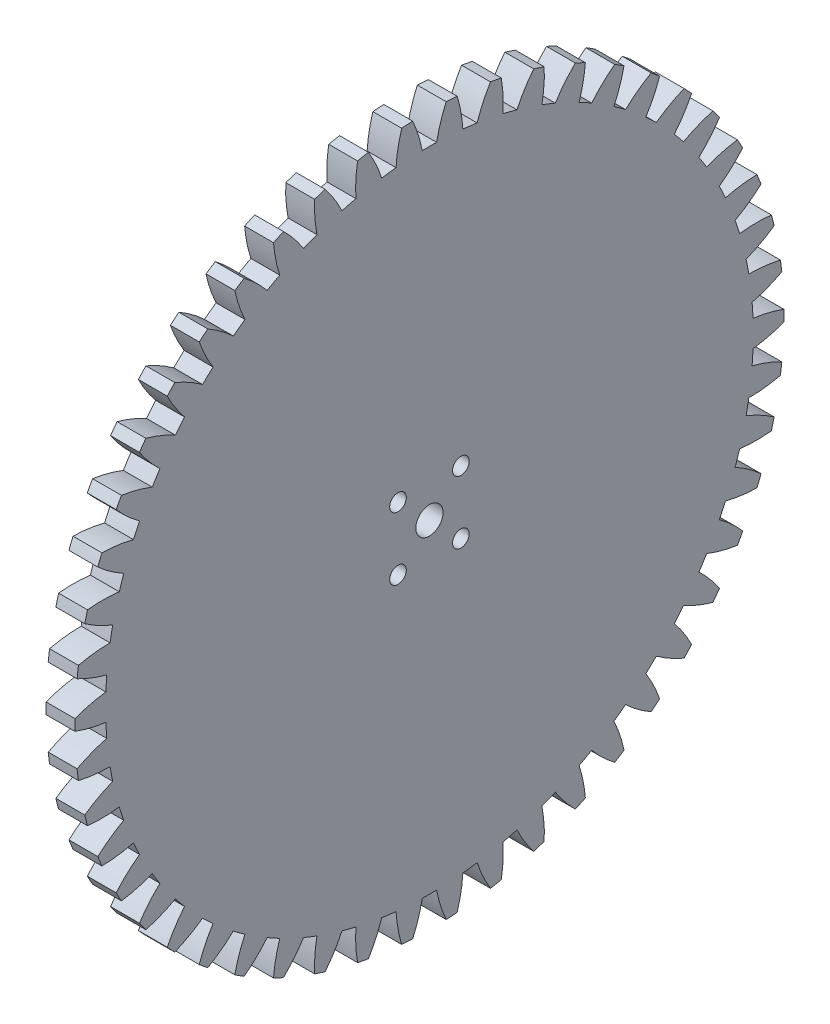
SolidWorks part; units mm, degrees
ref_plane "Plane1" through (0, 0, 0) normal (0, 0, 1) x (1, 0, 0)
ref_plane "Plane2" through (0, 0, 0) normal (0, 1, 0) x (1, 0, 0)
ref_plane "Plane3" through (0, 0, 0) normal (1, 0, 0) x (0, 0, -1)
sketch "HoldingSke" plane through (0, 0, 0) normal (0, 1, 0) x (1, 0, 0)
  line L0 (0, 0) -> (0.2143, -0.2553)
  line L1 (-15, 0) -> (100, 0) construction
  line L2 (0, 0) -> (-2.1039, 2.3779)
  line L3 (0, 0) -> (-11.863, 4.5341)
  line L4 (0, 0) -> (5.5511, 6.6156)
  line L5 (0, 0) -> (-46.8476, -17.4728)
  line L6 (0, 0) -> (-5.2639, -3.5516)
  line L7 (-2.1039, 2.3779) -> (8.6586, 51.2061)
  line L8 (-76.2, 54.61) -> (-75.2, 54.61)
  line L9 (-67.7845, 28.3722) -> (-49.3413, 33.142)
  line L10 (-76.2, 71.12) -> (104.1128, 71.12)
  line L11 (0, 0) -> (-6.35, 0)
  line L12 (-76.2, 101.6) -> (-76.093, 101.6)
  line L13 (24.9733, 27.94) -> (52.9518, 28.4284)
  line L14 (24.9733, 27.94) -> (24.9743, 27.94)
  line L15 (24.9733, 27.94) -> (100.4006, 29.5858)
  line L16 (-63.627, -3) -> (-12.827, -3)
  circle A0 centre (0, 0) radius 3
  circle A1 centre (0, 0) radius 37.5
  circle A2 centre (0, 0) radius 37.5
  circle A3 centre (0, 0) radius 3
  dimension "MHD" = 75
  dimension "Hub_dia" = 75
  dimension "Bore" = 6
  dimension "MBD" = 6
  dimension "Num_teeth" = 50
  dimension "Pitch" = 0.3333
  dimension "Overall_len" = 50
  dimension "Show_teeth" = 50
  dimension "Thickness" = 6.35
  dimension "OAL" = 50.0003
  dimension "T_dim" = 1
  dimension "Ap" = 14.5
  dimension "H" = 19.05
  dimension "Pitch_radius" = 180.3128
  dimension "Width" = 6.35
  dimension "Backlash" = 0.107
  dimension "Addendum_fac" = 1
  dimension "Dedendum_fac" = 1.25
  dimension "Clearance_fac" = 0.25
  dimension "Dedendum_add" = 0.001
  dimension "Module" = 3
sketch "BasProSke" plane through (0, 0, 0) normal (0, 1, 0) x (1, 0, 0)
  line L0 (-10, 0) -> (60, 0) construction
  line L1 (0, 0) -> (0, 78)
  line L2 (0, 0) -> (6.35, 0)
  line L3 (6.35, 0) -> (6.35, 78)
  line L4 (6.35, 78) -> (0, 78)
  dimension "Thickness" = 6.35
  dimension "Diameter" = 156
revolve "Base-Revolve" add sketch "BasProSke" angle 360 about L0
sketch "TooCutSke" plane through (0, 0, 0) normal (1, 0, 0) x (0, 0, -1)
  line L1 (0, 0) -> (0, 107) construction
  line L2 (0, 0) -> (-2.543, 74.9569) construction
  line L3 (0, 0) -> (-9.4146, 149.6414) construction
  line L4 (-2.543, 74.9569) -> (-4.7073, 74.8207) construction
  arc A0 (1.5844, 71.2314) -> (-1.5844, 71.2314) centre (0, 0) ccw
  arc A1 (3.6968, 77.9378) -> (-3.6968, 77.9378) centre (0, 0) ccw
  circle A2 centre (0, 0) radius 75 construction
  circle A3 centre (0, 0) radius 72.6111 construction
  arc A4 (-1.5844, 71.2314) -> (-3.6968, 77.9378) centre (-31.0576, 65.6338) ccw
  arc A5 (3.6968, 77.9378) -> (1.5844, 71.2314) centre (31.0576, 65.6338) ccw
  dimension "Root_dia" = 142.498
  dimension "Overcut_dia" = 156.0508
  dimension "Pitch_dia" = 150
  dimension "Base_dia" = 145.2221
  dimension "Flank_rad" = 30
  dimension "Half_ang" = 3.6
  dimension "Half_CT" = 2.1686
extrude "ToothCut" cut sketch "TooCutSke" along normal through all
fillet "Breaks" [suppressed] radius 0.06
fillet "RootFillets" [suppressed] radius 0.751
pattern_circular "TeethCuts" count 50 over 360 about axis through (0, 0, 0) along (1, 0, 0) of "ToothCut", "RootFillets", "Breaks"
sketch "HubNeaOneSke" plane through (0, 0, 0) normal (-1, 0, 0) x (0, 0, 1)
  circle A0 centre (0, 0) radius 37.5
  dimension "Diameter" = 75
extrude "HubNearOne" [suppressed] add sketch "HubNeaOneSke" along normal blind 43.6503
sketch "HubNeaBotSke" plane through (0, 0, 0) normal (-1, 0, 0) x (0, 0, 1)
  circle A0 centre (0, 0) radius 37.5
  dimension "Diameter" = 75
extrude "HubNearBoth" [suppressed] add sketch "HubNeaBotSke" along normal blind 21.8251
ref_plane "FarPln" through (6.35, 0, 0) normal (1, 0, 0) x (0, 0, -1)
sketch "HubFarSke" plane through (6.35, 0, 0) normal (1, 0, 0) x (0, 0, -1)
  circle A0 centre (0, 0) radius 37.5
  dimension "Diameter" = 75
extrude "HubFar" [suppressed] add sketch "HubFarSke" along normal blind 21.8251
sketch "BorSke" plane through (0, 0, 0) normal (1, 0, 0) x (0, 0, -1)
  circle A0 centre (0, 0) radius 3
  dimension "Diameter" = 6
extrude "Bore" cut sketch "BorSke" along normal mid plane 100.0005
sketch "KeySke" plane through (0, 0, 0) normal (1, 0, 0) x (0, 0, -1)
  line L0 (-1, 0) -> (-1, 4)
  line L1 (-1, 4) -> (1, 4)
  line L2 (1, 4) -> (1, 0)
  line L3 (0, 0) -> (0, 34) construction
  line L4 (-1, 0) -> (1, 0)
  dimension "Offset" = 4
  dimension "Width" = 2
extrude "Keyway" [suppressed] cut sketch "KeySke" along normal mid plane 100.0005
pattern_circular "Keyway2" [suppressed] count 2 every 90 about axis through (-10, 0, 0) along (1, 0, 0)
sketch "Esquisse1" plane through (0, 0, 0) normal (-1, 0, 0) x (0, 0, 1)
  circle A0 centre (6.9148, 6.9148) radius 1.83
  dimension "D1" = 3.66
extrude "Enlèv. mat.-Extru.1" cut sketch "Esquisse1" against normal up to next
pattern_circular "Répétition circulaire1" count 4 every 90 about axis through (0, 0, 0) along (1, 0, 0) of "Enlèv. mat.-Extru.1"
sketch "Esquisse2" plane through (6.35, 0, 0) normal (1, 0, 0) x (0, 0, -1)
  line L0 (-53, 25) -> (-8, 0)
  line L1 (-8, 0) -> (-53, -25)
  line L2 (-53, -25) -> (-53, 25) construction
  line L3 (-53, 0) -> (-8, 0) construction
  line L4 (50, 0) -> (-50, 0) construction
  circle A0 centre (0, 0) radius 3 construction
  spline S0 degree 2 poles (-53, 25) (-63, 0) (-53, -25) knots 0 0 0 1 1 1
  dimension "D4" = 8
  dimension "D1" = 45
  dimension "D2" = 50
  dimension "D3" = 5
extrude "Enlèv. mat.-Extru.2" [suppressed] cut sketch "Esquisse2" against normal up to next
fillet "Congé1" [suppressed] radius 2
pattern_circular "Répétition circulaire2" [suppressed] count 4 every 90
equation "' \"Module@HoldingSke\" = 6.35"
equation "' \"Num_teeth@HoldingSke\" = 12"
equation "' \"Ap@HoldingSke\" =  20"
equation "' \"Ap@HoldingSke\" = 20"
equation "' \"Width@HoldingSke\" = 0.5 * 25.4"
equation "' \"Hub_dia@HoldingSke\"= 1 * 25.4"
equation "' \"Hub_dia@HoldingSke\" = 1 * 25.4"
equation "' \"Overall_len@HoldingSke\" = 1.0 * 25.4"
equation "' \"Bore@HoldingSke\" = 0.75 * 25.4"
equation "' \"T_dim@HoldingSke\" = 0.1 * 25.4"
equation "' \"Width@KeySke\" = 0.25 * 25.4"
equation "' \"Show_teeth@HoldingSke\" = 13"
equation "' \"Backlash@HoldingSke\" = 0.009 * 25.4"
equation "' \"Addendum_fac@HoldingSke\" = 1.0"
equation "' \"Dedendum_fac@HoldingSke\" = 1.25"
equation "' \"Dedendum_add@HoldingSke\" = 0.00005 * 25.4"
equation "' \"Clearance_fac@HoldingSke\" = 0.25"
equation "\"Pitch@HoldingSke\" = 1 / \"Module@HoldingSke\""
equation "\"Overcut_dia@TooCutSke\" = (\"Num_teeth@HoldingSke\" + 2 * \"Addendum_fac@HoldingSke\") / \"Pitch@HoldingSke\" + 0.002 * 25.4"
equation "\"Pitch_dia@TooCutSke\" = \"Num_teeth@HoldingSke\" / \"Pitch@HoldingSke\""
equation "\"Base_dia@TooCutSke\" = \"Num_teeth@HoldingSke\" / \"Pitch@HoldingSke\" * cos((\"Ap@HoldingSke\"  * 3.14159265 / 180))"
equation "\"Root_dia@TooCutSke\" = (\"Num_teeth@HoldingSke\" + 2) / \"Pitch@HoldingSke\" - 2 * (\"Addendum_fac@HoldingSke\" + \"Dedendum_fac@HoldingSke\") / \"Pitch@HoldingSke\" - \"Dedendum_add@HoldingSke\" * 2"
equation "\"Half_ang@TooCutSke\" = 180 / \"Num_teeth@HoldingSke\""
equation "\"Half_CT@TooCutSke\" = \"Num_teeth@HoldingSke\" / \"Pitch@HoldingSke\" * sin((3.14159265 / 2 / \"Num_teeth@HoldingSke\")) / 2 - 7 * \"Backlash@HoldingSke\" / 4"
equation "\"Flank_rad@TooCutSke\" = \"Num_teeth@HoldingSke\" / \"Pitch@HoldingSke\" / 5"
equation "\"Radius@RootFillets\" = \"Clearance_fac@HoldingSke\" / \"Pitch@HoldingSke\" + \"Dedendum_add@HoldingSke\""
equation "\"Break_rad@Breaks\" = 0.02 / \"Pitch@HoldingSke\""
equation "\"Thickness@HoldingSke\" = \"Width@HoldingSke\""
equation "\"OAL@HoldingSke\" = \"Thickness@HoldingSke\""
equation "\"MHD@HoldingSke\" = (\"Num_teeth@HoldingSke\" + 2) / \"Pitch@HoldingSke\" - 2 * (\"Addendum_fac@HoldingSke\" + \"Dedendum_fac@HoldingSke\")  / \"Pitch@HoldingSke\" - \"Dedendum_add@HoldingSke\" * 2"
equation "\"MBD@HoldingSke\" = (\"Num_teeth@HoldingSke\" + 2) / \"Pitch@HoldingSke\" - 2 * (\"Addendum_fac@HoldingSke\" + \"Dedendum_fac@HoldingSke\")  / \"Pitch@HoldingSke\" - \"Dedendum_add@HoldingSke\" * 2 - 0.002 * 25.4"
equation "\"MHD@HoldingSke\" = ((sgn( \"MHD@HoldingSke\" - \"Hub_dia@HoldingSke\" )-1)*( \"MHD@HoldingSke\" - \"Hub_dia@HoldingSke\" ))/-2+ \"Hub_dia@HoldingSke\""
equation "\"MBD@HoldingSke\" = ((sgn( \"MBD@HoldingSke\" - \"Bore@HoldingSke\" )-1)*( \"MBD@HoldingSke\" - \"Bore@HoldingSke\" ))/-2+ \"Bore@HoldingSke\""
equation "\"OAL@HoldingSke\" = ((sgn( \"OAL@HoldingSke\" - \"Overall_len@HoldingSke\" )+1)*( \"OAL@HoldingSke\" - \"Overall_len@HoldingSke\" ))/2 + \"Overall_len@HoldingSke\" + 0.000002 * 25.4"
equation "\"Num_teeth@TeethCuts\" = int( \"Show_teeth@HoldingSke\" ) + 1"
equation "\"Num_teeth@TeethCuts\" = ((sgn( \"Num_teeth@TeethCuts\" - \"Num_teeth@HoldingSke\" )-1)*( \"Num_teeth@TeethCuts\" - \"Num_teeth@HoldingSke\" ))/-2+ \"Num_teeth@HoldingSke\""
equation "\"Num_teeth@TeethCuts\" = ((sgn( \"Num_teeth@TeethCuts\" - 2.0)+1)*( \"Num_teeth@TeethCuts\" - 2.0))/2 +2.0"
equation "\"Angle@TeethCuts\" = 360.0 / \"Num_teeth@HoldingSke\""
equation "\"Diameter@BasProSke\" = (\"Num_teeth@HoldingSke\" + 2 * \"Addendum_fac@HoldingSke\") / \"Pitch@HoldingSke\""
equation "\"Thickness@BasProSke\"  = \"Thickness@HoldingSke\""
equation "' \"Fillet_rad@BasProSke\" =  \"Thickness@HoldingSke\" * 0.05"
equation "' \"Fillet_rad@BasProSke\" = \"Thickness@HoldingSke\" * 0.05"
equation "\"MHD@HoldingSke\" = ((sgn( \"MHD@HoldingSke\" - \"Root_dia@TooCutSke\" )-1)*( \"MHD@HoldingSke\" - \"Root_dia@TooCutSke\" ))/-2+ \"Root_dia@TooCutSke\""
equation "\"Diameter@HubNeaOneSke\" = \"MHD@HoldingSke\""
equation "\"Length@HubNearOne\" = \"OAL@HoldingSke\" - \"Thickness@BasProSke\""
equation "\"Diameter@HubNeaBotSke\" = \"MHD@HoldingSke\""
equation "\"Length@HubNearBoth\" = ( \"OAL@HoldingSke\" - \"Thickness@BasProSke\" ) / 2.0"
equation "\"Thickness@FarPln\" = \"Thickness@BasProSke\""
equation "\"Diameter@HubFarSke\" = \"MHD@HoldingSke\""
equation "\"Length@HubFar\" = ( \"OAL@HoldingSke\" - \"Thickness@BasProSke\" ) / 2.0"
equation "\"Diameter@BorSke\" = \"MBD@HoldingSke\""
equation "\"D1@Bore\" = \"OAL@HoldingSke\" * 2.0"
equation "\"D1@Keyway\" = \"OAL@HoldingSke\" * 2.0"
equation "\"Offset@KeySke\" = \"T_dim@HoldingSke\" + \"MBD@HoldingSke\" / 2.0"
